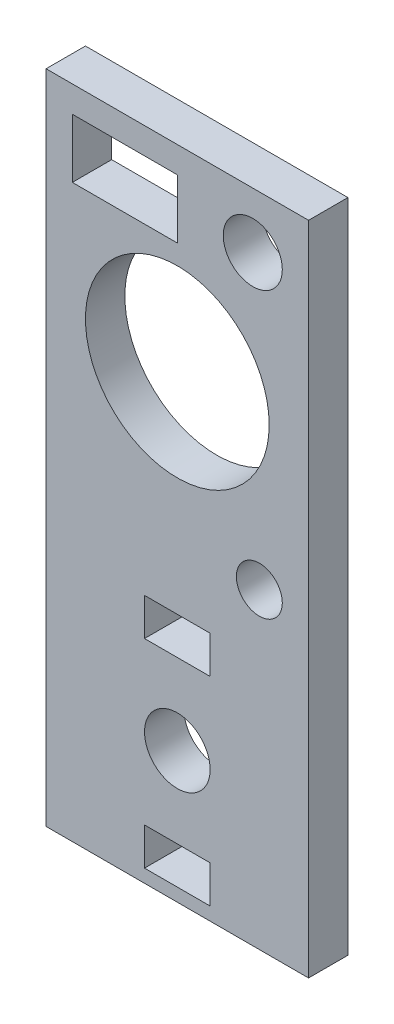
SolidWorks part; units mm, degrees
material "6061-T6 (SS)"
ref_plane "Front Plane" through (0, 0, 0) normal (0, 0, 1) x (1, 0, 0)
ref_plane "Top Plane" through (0, 0, 0) normal (0, 1, 0) x (1, 0, 0)
ref_plane "Right Plane" through (0, 0, 0) normal (1, 0, 0) x (0, 0, -1)
sketch "Sketch1" plane through (0, 0, 0) normal (0, 0, 1) x (1, 0, 0)
  line L0 (10, 48) -> (2, 43.5) construction
  line L1 (2, 48) -> (10, 48)
  line L2 (2, 48) -> (2, 43.5)
  line L3 (2, 43.5) -> (10, 43.5)
  line L4 (10, 48) -> (10, 43.5)
  line L5 (0, 35) -> (20, 35) construction
  line L6 (0, 20) -> (20, 20) construction
  line L7 (20, 20) -> (20, 0) construction
  line L8 (0, 50) -> (20, 50)
  line L9 (0, 50) -> (0, 0)
  line L10 (0, 0) -> (20, 0)
  line L11 (20, 50) -> (20, 0)
  line L12 (20, 20) -> (0, 0) construction
  line L13 (10, 50) -> (10, 0) construction
  line L14 (17, 42) -> (3, 42)
  line L15 (17, 42) -> (17, 28)
  line L16 (17, 28) -> (3, 28)
  line L17 (3, 42) -> (3, 28)
  line L18 (10, 10) -> (0, 10) construction
  line L19 (7.5, 1) -> (12.5, 1)
  line L20 (7.5, 1) -> (7.5, 3.85)
  line L21 (7.5, 3.85) -> (12.5, 3.85)
  line L22 (12.5, 1) -> (12.5, 3.85)
  line L23 (7.5, 19) -> (7.5, 16.15)
  line L24 (7.5, 19) -> (12.5, 19)
  line L25 (12.5, 19) -> (12.5, 16.15)
  line L26 (7.5, 16.15) -> (12.5, 16.15)
  circle A0 centre (16.25, 23.75) radius 1.75
  circle A1 centre (15.75, 45.75) radius 2.25
  circle A2 centre (10, 10) radius 2.5
  circle A3 centre (10, 35) radius 7
  point P9 (6, 45.75)
  point P12 (15.75, 48)
  point P15 (15.75, 43.5)
  point P17 (18, 45.75)
  point P20 (18, 23.75)
  point P21 (16.25, 22)
  point P31 (17, 35)
  point P32 (10, 28)
  dimension "D1" = 3.5
  dimension "D4" = 4.5
  dimension "D6" = 2
  dimension "D14" = 5
  dimension "D2" = 4.5
  dimension "D3" = 8
  dimension "D5" = 2
  dimension "D7" = 20
  dimension "D8" = 2
  dimension "D9" = 2
  dimension "D10" = 50
  dimension "D11" = 2
  dimension "D12" = 22
  dimension "D13" = 20
  dimension "D15" = 14
  dimension "D16" = 14
  dimension "D17" = 35
  dimension "D18" = 7.5
  dimension "D19" = 1
  dimension "D20" = 2.85
  dimension "D21" = 5
extrude "Boss-Extrude1" add sketch "Sketch1" along normal blind 3 contours L11 L8 L9 L10 A2 A1 A0 L17 L14 L15 L16 L1 L4 L3 L2 | A3 L17 L16 | A3 L16 L15 | A3 L15 L14 | A3 L14 L17
